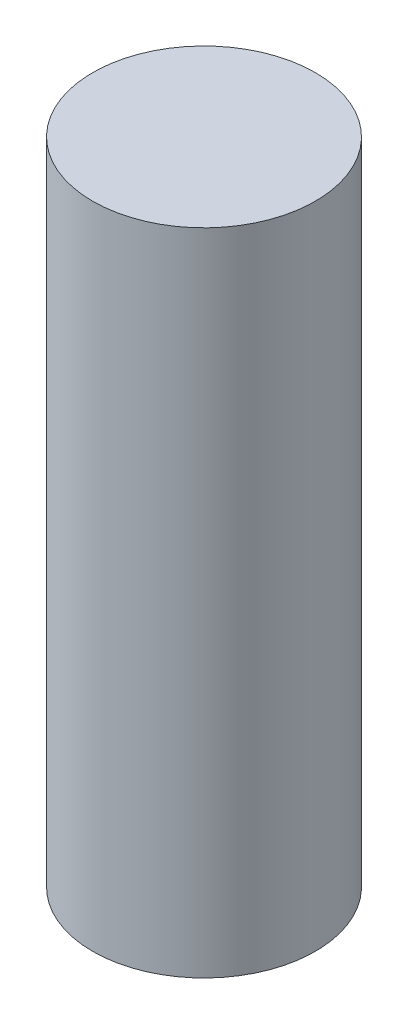
SolidWorks part; units mm, degrees
ref_plane "Front Plane" through (0, 0, 0) normal (0, 0, 1) x (1, 0, 0)
ref_plane "Top Plane" through (0, 0, 0) normal (0, 1, 0) x (1, 0, 0)
ref_plane "Right Plane" through (0, 0, 0) normal (1, 0, 0) x (0, 0, -1)
sketch "Sketch1" plane through (0, 0, 0) normal (0, 1, 0) x (1, 0, 0)
  circle A0 centre (0, 0) radius 152.4
  dimension "D1" = 304.8
extrude "Boss-Extrude1" add sketch "Sketch1" along normal blind 889 contours A0
